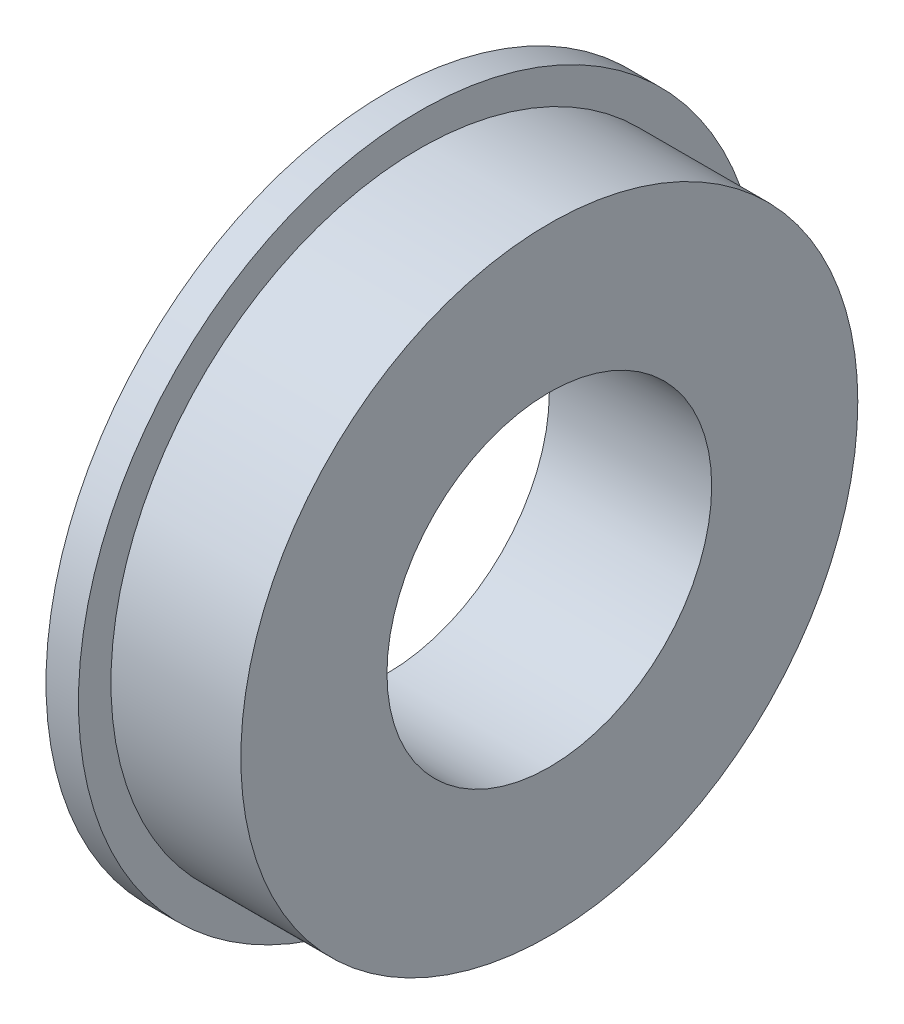
SolidWorks part; units mm, degrees
material "AISI 304"
ref_plane "前视基准面" through (0, 0, 0) normal (0, 0, 1) x (1, 0, 0)
ref_plane "上视基准面" through (0, 0, 0) normal (0, 1, 0) x (1, 0, 0)
ref_plane "右视基准面" through (0, 0, 0) normal (1, 0, 0) x (0, 0, -1)
sketch "草图1" plane through (0, 0, 0) normal (1, 0, 0) x (0, 0, -1)
  line L0 (-23.9568, 0) -> (22.2718, 0) construction
  line L1 (0, 25.1553) -> (0, -22.3288) construction
  circle A0 centre (0, 0) radius 10.5
  circle A1 centre (0, 0) radius 5
extrude "凸台-拉伸1" add sketch "草图1" along normal blind 5
sketch "草图3" plane through (5, 0, 0) normal (1, 0, 0) x (0, 0, -1)
  circle A0 centre (0, 0) radius 10.5
  circle A1 centre (0, 0) radius 9.5
extrude "切除-拉伸1" cut sketch "草图3" against normal blind 4
